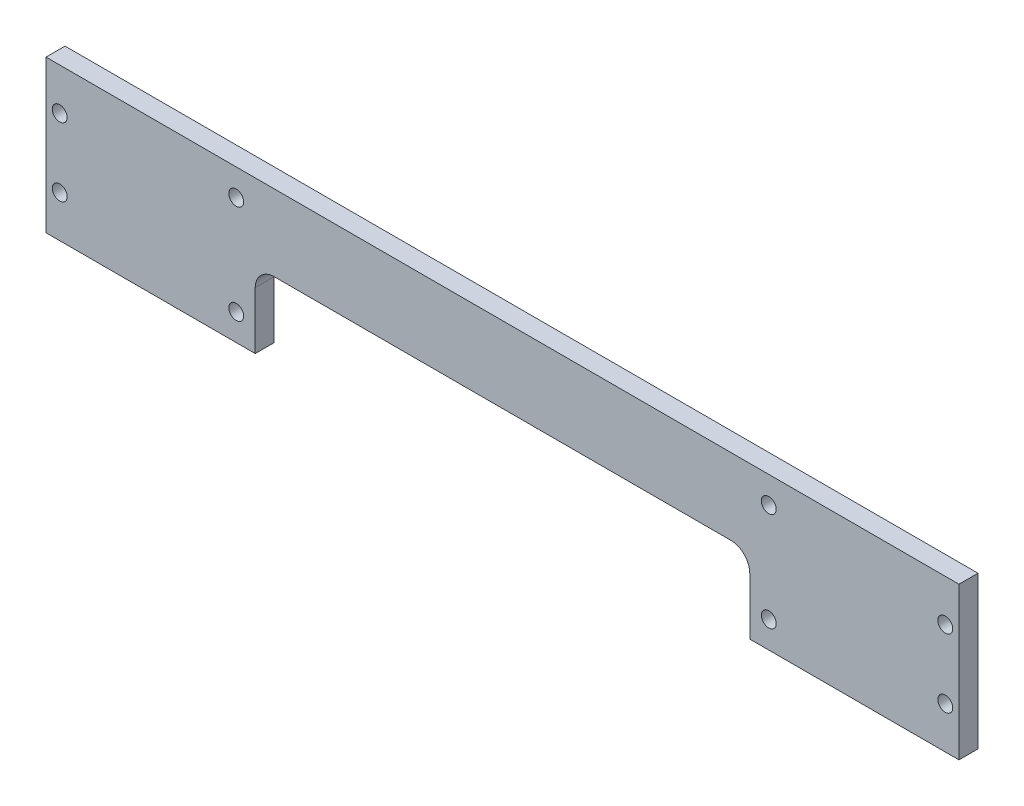
SolidWorks part; units mm, degrees
material "6061-T6 (SS)"
ref_plane "Front Plane" through (0, 0, 0) normal (0, 0, 1) x (1, 0, 0)
ref_plane "Top Plane" through (0, 0, 0) normal (0, 1, 0) x (1, 0, 0)
ref_plane "Right Plane" through (0, 0, 0) normal (1, 0, 0) x (0, 0, -1)
sketch "Sketch1" plane through (0, 0, 0) normal (0, 0, 1) x (1, 0, 0)
  line L1 (-152.4, 25.4) -> (152.4, 25.4)
  line L2 (-152.4, 25.4) -> (-152.4, -25.4)
  line L3 (-152.4, -25.4) -> (152.4, -25.4)
  line L4 (152.4, 25.4) -> (152.4, -25.4)
  line L5 (-152.4, 25.4) -> (152.4, -25.4) construction
  line L6 (-152.4, -25.4) -> (152.4, 25.4) construction
  line L7 (-88.9, 16.51) -> (88.9, 16.51) construction
  line L8 (-88.9, 16.51) -> (-88.9, -16.51) construction
  line L9 (-88.9, -16.51) -> (88.9, -16.51) construction
  line L10 (88.9, 16.51) -> (88.9, -16.51) construction
  line L11 (-88.9, 16.51) -> (88.9, -16.51) construction
  line L12 (-88.9, -16.51) -> (88.9, 16.51) construction
  line L13 (147.828, -11.43) -> (-147.828, -11.43) construction
  line L14 (147.828, -11.43) -> (147.828, 11.43) construction
  line L15 (147.828, 11.43) -> (-147.828, 11.43) construction
  line L16 (-147.828, -11.43) -> (-147.828, 11.43) construction
  line L17 (147.828, -11.43) -> (-147.828, 11.43) construction
  line L18 (147.828, 11.43) -> (-147.828, -11.43) construction
  circle A0 centre (-88.9, 16.51) radius 2.4892
  circle A1 centre (-88.9, -16.51) radius 2.4892
  circle A2 centre (88.9, -16.51) radius 2.4892
  circle A3 centre (88.9, 16.51) radius 2.4892
  circle A4 centre (-147.828, 11.43) radius 2.4892
  circle A5 centre (-147.828, -11.43) radius 2.4892
  circle A6 centre (147.828, 11.43) radius 2.4892
  circle A7 centre (147.828, -11.43) radius 2.4892
  point P0 (0, 0)
  point P6 (0, 0)
  point P15 (0, 0)
  dimension "D5" = 4.9784
  dimension "D8" = 4.9784
  dimension "D1" = 50.8
  dimension "D2" = 304.8
  dimension "D3" = 63.5
  dimension "D4" = 33.02
  dimension "D6" = 4.572
  dimension "D7" = 13.97
extrude "Boss-Extrude1" add sketch "Sketch1" along normal blind 6.35
sketch "Sketch3" plane through (0, 0, 6.35) normal (0, 0, 1) x (1, 0, 0)
  line L0 (-152.4, -25.4) -> (152.4, -25.4) construction
  line L1 (-82.55, -25.4) -> (82.55, -25.4)
  line L2 (-82.55, -25.4) -> (-82.55, 0)
  line L3 (-82.55, 0) -> (82.55, 0)
  line L4 (82.55, -25.4) -> (82.55, 0)
  line L5 (-152.4, 25.4) -> (-152.4, -25.4) construction
  point P8 (0, 0)
  dimension "D1" = 69.85
  dimension "D2" = 25.4
extrude "Cut-Extrude1" cut sketch "Sketch3" against normal through all
fillet "Fillet1" radius 6.35 2 edges at (82.55, 0, 3.175) (-82.55, 0, 3.175)
